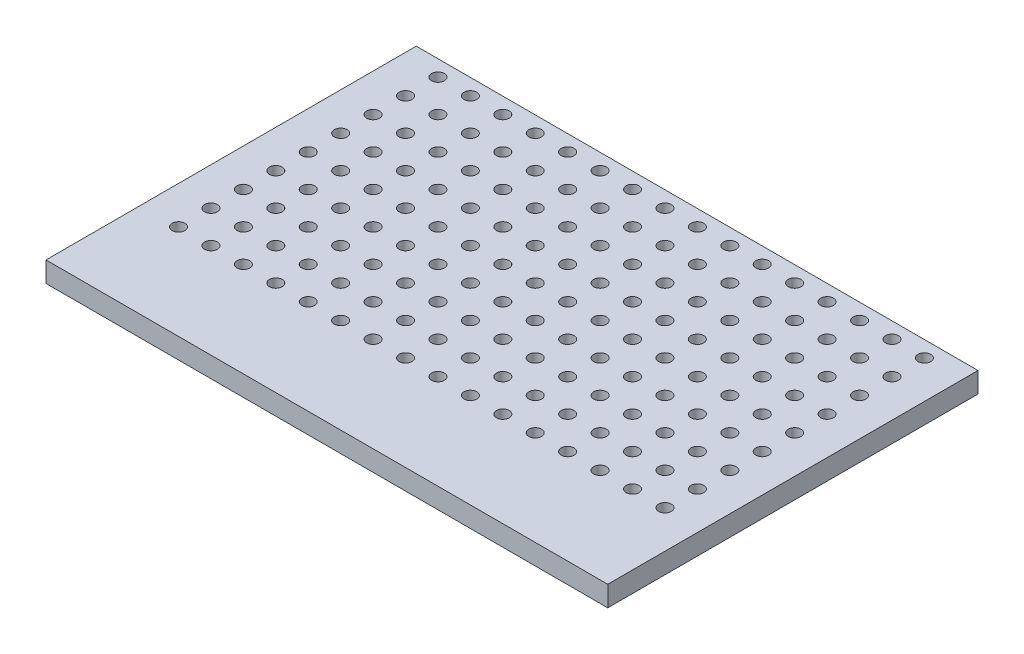
SolidWorks part; units mm, degrees
ref_plane "Front Plane" through (0, 0, 0) normal (0, 0, 1) x (1, 0, 0)
ref_plane "Top Plane" through (0, 0, 0) normal (0, 1, 0) x (1, 0, 0)
ref_plane "Right Plane" through (0, 0, 0) normal (1, 0, 0) x (0, 0, -1)
sketch "Sketch1" plane through (0, 0, 0) normal (0, 1, 0) x (1, 0, 0)
  line L0 (0, 14.5) -> (0, -14.5) construction
  line L1 (-22, 14.5) -> (22, 14.5)
  line L2 (-22, 14.5) -> (-22, -14.5)
  line L3 (-22, -14.5) -> (22, -14.5)
  line L4 (22, 14.5) -> (22, -14.5)
  line L5 (-22, 14.5) -> (22, -14.5) construction
  line L6 (-22, -14.5) -> (22, 14.5) construction
  circle A0 centre (1.27, 13.25) radius 0.5
  circle A1 centre (3.81, 13.25) radius 0.5
  circle A2 centre (6.35, 13.25) radius 0.5
  circle A3 centre (8.89, 13.25) radius 0.5
  circle A4 centre (11.43, 13.25) radius 0.5
  circle A5 centre (13.97, 13.25) radius 0.5
  circle A6 centre (16.51, 13.25) radius 0.5
  circle A7 centre (19.05, 13.25) radius 0.5
  circle A8 centre (3.81, 10.71) radius 0.5
  circle A9 centre (6.35, 10.71) radius 0.5
  circle A10 centre (8.89, 10.71) radius 0.5
  circle A11 centre (11.43, 10.71) radius 0.5
  circle A12 centre (13.97, 10.71) radius 0.5
  circle A13 centre (16.51, 10.71) radius 0.5
  circle A14 centre (19.05, 10.71) radius 0.5
  circle A15 centre (3.81, 8.17) radius 0.5
  circle A16 centre (6.35, 8.17) radius 0.5
  circle A17 centre (8.89, 8.17) radius 0.5
  circle A18 centre (11.43, 8.17) radius 0.5
  circle A19 centre (13.97, 8.17) radius 0.5
  circle A20 centre (16.51, 8.17) radius 0.5
  circle A21 centre (19.05, 8.17) radius 0.5
  circle A22 centre (3.81, 5.63) radius 0.5
  circle A23 centre (6.35, 5.63) radius 0.5
  circle A24 centre (8.89, 5.63) radius 0.5
  circle A25 centre (11.43, 5.63) radius 0.5
  circle A26 centre (13.97, 5.63) radius 0.5
  circle A27 centre (16.51, 5.63) radius 0.5
  circle A28 centre (19.05, 5.63) radius 0.5
  circle A29 centre (3.81, 3.09) radius 0.5
  circle A30 centre (6.35, 3.09) radius 0.5
  circle A31 centre (8.89, 3.09) radius 0.5
  circle A32 centre (11.43, 3.09) radius 0.5
  circle A33 centre (13.97, 3.09) radius 0.5
  circle A34 centre (16.51, 3.09) radius 0.5
  circle A35 centre (19.05, 3.09) radius 0.5
  circle A36 centre (3.81, 0.55) radius 0.5
  circle A37 centre (6.35, 0.55) radius 0.5
  circle A38 centre (8.89, 0.55) radius 0.5
  circle A39 centre (11.43, 0.55) radius 0.5
  circle A40 centre (13.97, 0.55) radius 0.5
  circle A41 centre (16.51, 0.55) radius 0.5
  circle A42 centre (19.05, 0.55) radius 0.5
  circle A43 centre (3.81, -1.99) radius 0.5
  circle A44 centre (6.35, -1.99) radius 0.5
  circle A45 centre (8.89, -1.99) radius 0.5
  circle A46 centre (11.43, -1.99) radius 0.5
  circle A47 centre (13.97, -1.99) radius 0.5
  circle A48 centre (16.51, -1.99) radius 0.5
  circle A49 centre (19.05, -1.99) radius 0.5
  circle A50 centre (3.81, -4.53) radius 0.5
  circle A51 centre (6.35, -4.53) radius 0.5
  circle A52 centre (8.89, -4.53) radius 0.5
  circle A53 centre (11.43, -4.53) radius 0.5
  circle A54 centre (13.97, -4.53) radius 0.5
  circle A55 centre (16.51, -4.53) radius 0.5
  circle A56 centre (19.05, -4.53) radius 0.5
  circle A57 centre (3.81, -7.07) radius 0.5
  circle A58 centre (6.35, -7.07) radius 0.5
  circle A59 centre (8.89, -7.07) radius 0.5
  circle A60 centre (11.43, -7.07) radius 0.5
  circle A61 centre (13.97, -7.07) radius 0.5
  circle A62 centre (16.51, -7.07) radius 0.5
  circle A63 centre (19.05, -7.07) radius 0.5
  circle A64 centre (1.27, 10.71) radius 0.5
  circle A65 centre (1.27, 8.17) radius 0.5
  circle A66 centre (1.27, 5.63) radius 0.5
  circle A67 centre (1.27, 3.09) radius 0.5
  circle A68 centre (1.27, 0.55) radius 0.5
  circle A69 centre (1.27, -1.99) radius 0.5
  circle A70 centre (1.27, -4.53) radius 0.5
  circle A71 centre (1.27, -7.07) radius 0.5
  circle A72 centre (-1.27, -7.07) radius 0.5
  circle A73 centre (-1.27, -4.53) radius 0.5
  circle A74 centre (-1.27, -1.99) radius 0.5
  circle A75 centre (-1.27, 0.55) radius 0.5
  circle A76 centre (-1.27, 3.09) radius 0.5
  circle A77 centre (-1.27, 5.63) radius 0.5
  circle A78 centre (-1.27, 8.17) radius 0.5
  circle A79 centre (-1.27, 10.71) radius 0.5
  circle A80 centre (-19.05, -7.07) radius 0.5
  circle A81 centre (-16.51, -7.07) radius 0.5
  circle A82 centre (-13.97, -7.07) radius 0.5
  circle A83 centre (-11.43, -7.07) radius 0.5
  circle A84 centre (-8.89, -7.07) radius 0.5
  circle A85 centre (-6.35, -7.07) radius 0.5
  circle A86 centre (-3.81, -7.07) radius 0.5
  circle A87 centre (-19.05, -4.53) radius 0.5
  circle A88 centre (-16.51, -4.53) radius 0.5
  circle A89 centre (-13.97, -4.53) radius 0.5
  circle A90 centre (-11.43, -4.53) radius 0.5
  circle A91 centre (-8.89, -4.53) radius 0.5
  circle A92 centre (-6.35, -4.53) radius 0.5
  circle A93 centre (-3.81, -4.53) radius 0.5
  circle A94 centre (-19.05, -1.99) radius 0.5
  circle A95 centre (-16.51, -1.99) radius 0.5
  circle A96 centre (-13.97, -1.99) radius 0.5
  circle A97 centre (-11.43, -1.99) radius 0.5
  circle A98 centre (-8.89, -1.99) radius 0.5
  circle A99 centre (-6.35, -1.99) radius 0.5
  circle A100 centre (-3.81, -1.99) radius 0.5
  circle A101 centre (-19.05, 0.55) radius 0.5
  circle A102 centre (-16.51, 0.55) radius 0.5
  circle A103 centre (-13.97, 0.55) radius 0.5
  circle A104 centre (-11.43, 0.55) radius 0.5
  circle A105 centre (-8.89, 0.55) radius 0.5
  circle A106 centre (-6.35, 0.55) radius 0.5
  circle A107 centre (-3.81, 0.55) radius 0.5
  circle A108 centre (-19.05, 3.09) radius 0.5
  circle A109 centre (-16.51, 3.09) radius 0.5
  circle A110 centre (-13.97, 3.09) radius 0.5
  circle A111 centre (-11.43, 3.09) radius 0.5
  circle A112 centre (-8.89, 3.09) radius 0.5
  circle A113 centre (-6.35, 3.09) radius 0.5
  circle A114 centre (-3.81, 3.09) radius 0.5
  circle A115 centre (-19.05, 5.63) radius 0.5
  circle A116 centre (-16.51, 5.63) radius 0.5
  circle A117 centre (-13.97, 5.63) radius 0.5
  circle A118 centre (-11.43, 5.63) radius 0.5
  circle A119 centre (-8.89, 5.63) radius 0.5
  circle A120 centre (-6.35, 5.63) radius 0.5
  circle A121 centre (-3.81, 5.63) radius 0.5
  circle A122 centre (-19.05, 8.17) radius 0.5
  circle A123 centre (-16.51, 8.17) radius 0.5
  circle A124 centre (-13.97, 8.17) radius 0.5
  circle A125 centre (-11.43, 8.17) radius 0.5
  circle A126 centre (-8.89, 8.17) radius 0.5
  circle A127 centre (-6.35, 8.17) radius 0.5
  circle A128 centre (-3.81, 8.17) radius 0.5
  circle A129 centre (-19.05, 10.71) radius 0.5
  circle A130 centre (-16.51, 10.71) radius 0.5
  circle A131 centre (-13.97, 10.71) radius 0.5
  circle A132 centre (-11.43, 10.71) radius 0.5
  circle A133 centre (-8.89, 10.71) radius 0.5
  circle A134 centre (-6.35, 10.71) radius 0.5
  circle A135 centre (-3.81, 10.71) radius 0.5
  circle A136 centre (-19.05, 13.25) radius 0.5
  circle A137 centre (-16.51, 13.25) radius 0.5
  circle A138 centre (-13.97, 13.25) radius 0.5
  circle A139 centre (-11.43, 13.25) radius 0.5
  circle A140 centre (-8.89, 13.25) radius 0.5
  circle A141 centre (-6.35, 13.25) radius 0.5
  circle A142 centre (-3.81, 13.25) radius 0.5
  circle A143 centre (-1.27, 13.25) radius 0.5
  point P0 (0, 0)
  dimension "D3" = 1
  dimension "D1" = 29
  dimension "D2" = 44
  dimension "D4" = 1.25
  dimension "D5" = 1.27
  dimension "D6" = 8
  dimension "D7" = 9
extrude "Boss-Extrude1" add sketch "Sketch1" along normal blind 1.6
